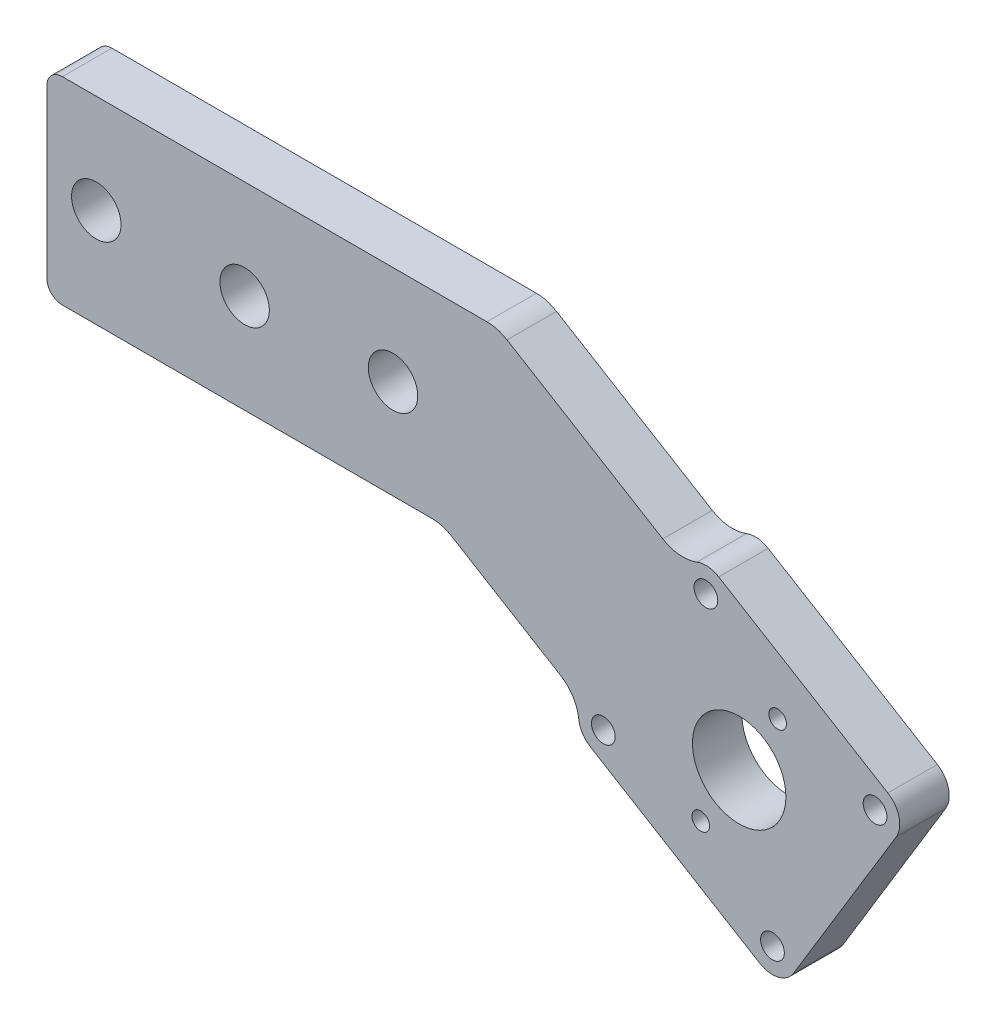
SolidWorks part; units mm, degrees
ref_plane "Front Plane" through (0, 0, 0) normal (0, 0, 1) x (1, 0, 0)
ref_plane "Top Plane" through (0, 0, 0) normal (0, 1, 0) x (1, 0, 0)
ref_plane "Right Plane" through (0, 0, 0) normal (1, 0, 0) x (0, 0, -1)
sketch "Sketch1" plane through (0, 0, 0) normal (0, 0, 1) x (1, 0, 0)
  line L0 (-50.8, 0) -> (28.0438, 0) construction
  line L2 (-50.8, -12.7) -> (-50.8, 12.7) construction
  line L5 (33.1614, -29.0947) -> (31.5152, -31.8096) construction
  line L6 (44.6848, -10.0904) -> (7.0992, 12.7) construction
  line L19 (0, -12.7) -> (0, 12.7) construction
  line L28 (43.0386, -12.8053) -> (44.6848, -10.0904) construction
  line L31 (43.0386, -12.8053) -> (33.1614, -29.0947) construction
  line L32 (-48.8, 12.7) -> (-48.8, -12.7) construction
  line L33 (-50.8, 12.7) -> (7.0992, 12.7) construction
  line L34 (0, -12.7) -> (-50.8, -12.7) construction
  line L35 (-50.8, 10.7) -> (-50.8, -10.7)
  line L36 (7.0992, 12.7) -> (-48.8, 12.7)
  line L37 (-48.8, -12.7) -> (0, -12.7)
  line L38 (31.5152, -31.8096) -> (0, -12.7) construction
  line L39 (40.7286, -41.1093) -> (19.0094, -27.9396)
  line L42 (57.1906, -13.9604) -> (35.4715, -0.7907)
  line L43 (42.3748, -38.3944) -> (55.5444, -16.6752) construction
  line L44 (58.2593, -18.3214) -> (45.0896, -40.0406)
  line L49 (20.6556, -25.2248) -> (42.3748, -38.3944) construction
  line L50 (33.8252, -3.5056) -> (20.6556, -25.2248) construction
  line L51 (33.8252, -3.5056) -> (55.5444, -16.6752) construction
  line L52 (31.1104, -1.8594) -> (7.0992, 12.7)
  line L53 (17.9407, -23.5785) -> (0, -12.7)
  circle A13 centre (38.1, -20.95) radius 6
  circle A17 centre (43.0386, -12.8053) radius 1.1303
  circle A18 centre (33.1614, -29.0947) radius 1.1303
  circle A19 centre (-6.35, 0) radius 3.175
  circle A20 centre (-25.4, 0) radius 3.175
  circle A21 centre (-44.45, 0) radius 3.175
  arc A22 (-48.8, 12.7) -> (-50.8, 10.7) centre (-48.8, 10.7) ccw
  arc A23 (-48.8, -12.7) -> (-50.8, -10.7) centre (-48.8, -10.7) cw
  circle A25 centre (33.8252, -3.5056) radius 1.524
  circle A26 centre (20.6556, -25.2248) radius 1.524
  circle A27 centre (42.3748, -38.3944) radius 1.524
  circle A28 centre (55.5444, -16.6752) radius 1.524
  arc A30 (57.1906, -13.9604) -> (58.2593, -18.3214) centre (55.5444, -16.6752) cw
  arc A31 (45.0896, -40.0406) -> (40.7286, -41.1093) centre (42.3748, -38.3944) cw
  arc A32 (35.4715, -0.7907) -> (31.1104, -1.8594) centre (33.8252, -3.5056) ccw
  arc A33 (19.0094, -27.9396) -> (17.9407, -23.5785) centre (20.6556, -25.2248) cw
  point P10 (0, 0)
  point P32 (-48.8, -10.7)
  point P33 (-48.8, 10.7)
  dimension "D4" = 25.4
  dimension "D7" = 25.4
  dimension "D8" = 3.048
  dimension "D10" = 31.75
  dimension "D5" = 19.05
  dimension "D6" = 19.05
  dimension "D9" = 12
  dimension "D14" = 2.2606
  dimension "D12" = 25.4
  dimension "D18" = 6.35
  dimension "D20" = 3.175
  dimension "D2" = 20.95
  dimension "D3" = 38.1
  dimension "D11" = 19.05
  dimension "D13" = 25.4
  dimension "D15" = 2
  dimension "D16" = 2
  dimension "D17" = 2
  dimension "D19" = 3.175
  dimension "D21" = 3.175
  dimension "D22" = 25.4
extrude "Boss-Extrude1" add sketch "Sketch1" along normal blind 6.35
fillet "Fillet1" radius 5 4 edges at (0, -12.7, 3.175) (7.0992, 12.7, 3.175) (17.9407, -23.5785, 3.175) (31.1104, -1.8594, 3.175)
